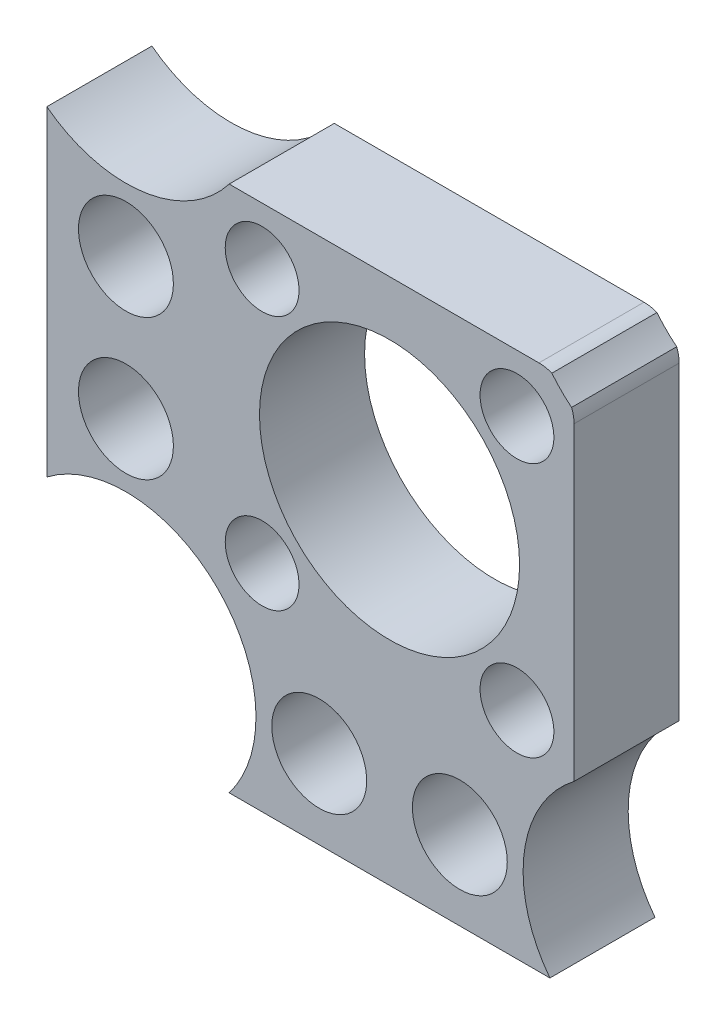
SolidWorks part; units mm, degrees
ref_plane "Front Plane" through (0, 0, 0) normal (0, 0, 1) x (1, 0, 0)
ref_plane "Top Plane" through (0, 0, 0) normal (0, 1, 0) x (1, 0, 0)
ref_plane "Right Plane" through (0, 0, 0) normal (1, 0, 0) x (0, 0, -1)
sketch "Sketch1" plane through (0, 0, 0) normal (0, 0, 1) x (1, 0, 0)
  line L0 (10.5, -19.5) -> (-2.5, -10.5) construction
  line L1 (-9.1255, -10.5) -> (9.1255, -10.5) construction
  line L2 (0, 6.6) -> (0, -6.6) construction
  line L3 (-10.5, -10.5) -> (10.5, 10.5) construction
  line L12 (-10.5, -10.5) -> (-10.5, -19.5)
  line L13 (-10.5, -19.5) -> (10.5, -19.5)
  line L14 (10.5, -19.5) -> (10.5, 10.5)
  line L15 (10.5, 10.5) -> (-19.5, 10.5)
  line L16 (-19.5, 10.5) -> (-19.5, -10.5)
  line L17 (-19.5, -10.5) -> (-10.5, -10.5)
  circle A0 centre (4, -15) radius 2.7 construction
  circle A1 centre (0, 0) radius 7.4 construction
  circle A3 centre (0, 0) radius 7.4
  dimension "D3" = 5.4
  dimension "D2" = 2.5
  dimension "D4" = 30
  dimension "D1" = 30
  dimension "D5" = 21
  dimension "D6" = 21
extrude "Boss-Extrude1" add sketch "Sketch1" against normal offset from surface (5.98 mm away) 0.02
sketch "Sketch2" plane through (0, 0, -5.98) normal (0, 0, -1) x (-1, 0, 0)
  line L0 (-10.5, 10.5) -> (-4, 4) construction
  line L1 (0, 0) -> (-4, 4) construction
  circle A2 centre (-7.25, 7.25) radius 2.1
  point P7 (-7.25, 7.25)
  dimension "D1" = 4.2
  dimension "D2" = 4
extrude "Cut-Extrude1" cut sketch "Sketch2" against normal up to next
pattern_circular "CirPattern1" count 4 over 360 about axis through (0, 0, 0) along (0, 0, 1) of "Cut-Extrude1"
fillet "Fillet1" radius 7 1 edges at (-10.5, -10.5, -2.99)
sketch "Sketch3" plane through (0, 0, -5.98) normal (0, 0, -1) x (-1, 0, 0)
  line L0 (0, 0) -> (30, -30)
  circle A0 centre (15, -15) radius 7.4
  line M6 (17.5, -10.5) -> (19.5, -10.5)
  line M7 (19.5, -10.5) -> (19.5, 10.5)
  line M10 (-10.5, -19.5) -> (10.5, -19.5)
  line M11 (10.5, -19.5) -> (10.5, -17.5)
  arc M12 (10.5, -17.5) -> (17.5, -10.5) centre (17.5, -17.5) cw
  dimension "D3" = 14.8
  dimension "D1" = 30
  dimension "D2" = 30
extrude "Cut-Extrude2" cut sketch "Sketch3" against normal blind 11 contours A0 L0 M7 M12 M6 | L0 A0 M10 M11 M12 | A0 L0 M10 M12 M11 | L0 A0 M7 M6 M12
fillet "Fillet2" radius 2 1 edges at (10.5, 10.5, -2.99)
pattern_circular "CirPattern2" count 4 over 360 about axis through (0, 0, 0) along (0, 0, 1) of "Cut-Extrude2"
sketch "Sketch4" plane through (0, 0, 0) normal (0, 0, 1) x (1, 0, 0)
  circle A0 centre (4, -15) radius 2.7 construction
  circle A1 centre (4, -15) radius 2.7
extrude "Cut-Extrude3" cut sketch "Sketch4" against normal up to next
mirror "Mirror1" about plane through (0, 0, 0) normal (1, 0, 0) of "Cut-Extrude3"
pattern_circular "CirPattern3" count 2 every 90 about axis through (0, 0, -48.4264) along (0, 0, 1) of "Cut-Extrude3", "Mirror1"
